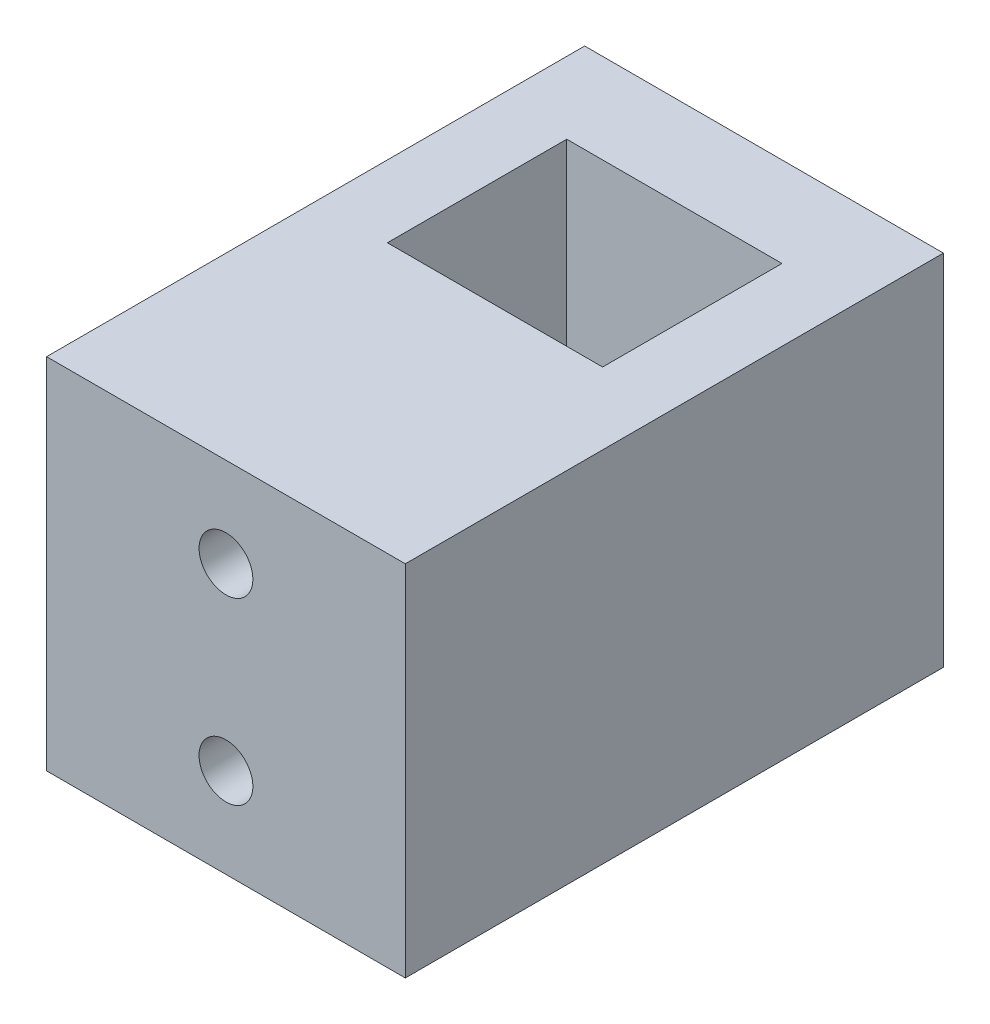
SolidWorks part; units mm, degrees
ref_plane "Front Plane" through (0, 0, 0) normal (0, 0, 1) x (1, 0, 0)
ref_plane "Top Plane" through (0, 0, 0) normal (0, 1, 0) x (1, 0, 0)
ref_plane "Right Plane" through (0, 0, 0) normal (1, 0, 0) x (0, 0, -1)
sketch "Sketch1" plane through (0, 0, 0) normal (0, 1, 0) x (1, 0, 0)
  line L0 (0, 0) -> (0, 37.0003) construction
  line L2 (-10, 30) -> (10, 30)
  line L3 (-10, 30) -> (-10, 0)
  line L4 (-10, 0) -> (10, 0)
  line L5 (10, 30) -> (10, 0)
  line L6 (-10, 30) -> (10, 0) construction
  line L7 (-10, 0) -> (10, 30) construction
  point P2 (0, 15)
  dimension "D1" = 20
  dimension "D2" = 0
  dimension "D3" = 30
extrude "Boss-Extrude1" add sketch "Sketch1" along normal blind 20
sketch "Sketch4" plane through (0, 20, 0) normal (0, 1, 0) x (1, 0, 0)
  line L0 (0, 0) -> (0, 49.3) construction
  line L1 (-10, 0) -> (10, 0) construction
  line L3 (-6, 25) -> (6, 25)
  line L4 (-6, 25) -> (-6, 15)
  line L5 (-6, 15) -> (6, 15)
  line L6 (6, 25) -> (6, 15)
  line L7 (-6, 25) -> (6, 15) construction
  line L8 (-6, 15) -> (6, 25) construction
  point P4 (0, 20)
  dimension "D1" = 12
  dimension "D2" = 10
  dimension "D3" = 20
extrude "Cut-Extrude2" cut sketch "Sketch4" against normal blind 18
sketch "Sketch3" plane through (0, 0, 0) normal (0, 1, 0) x (1, 0, 0)
  line L0 (0, 0) -> (0, 40) construction
  circle A0 centre (0, 20) radius 1.5
  dimension "D1" = 3
  dimension "D2" = 20
extrude "Cut-Extrude3" cut sketch "Sketch3" along normal through all
sketch "Sketch5" plane through (0, 0, 0) normal (0, 0, 1) x (1, 0, 0)
  line L0 (0, 20) -> (0, 0) construction
  line L3 (-10, 20) -> (10, 20) construction
  line L4 (-10, 10) -> (10, 10) construction
  line L5 (-10, 20) -> (-10, 0) construction
  line L6 (10, 20) -> (10, 0) construction
  circle A0 centre (0, 15) radius 1.5
  circle A1 centre (0, 5) radius 1.5
  dimension "D1" = 3
  dimension "D2" = 10
extrude "Cut-Extrude4" cut sketch "Sketch5" against normal blind 10
